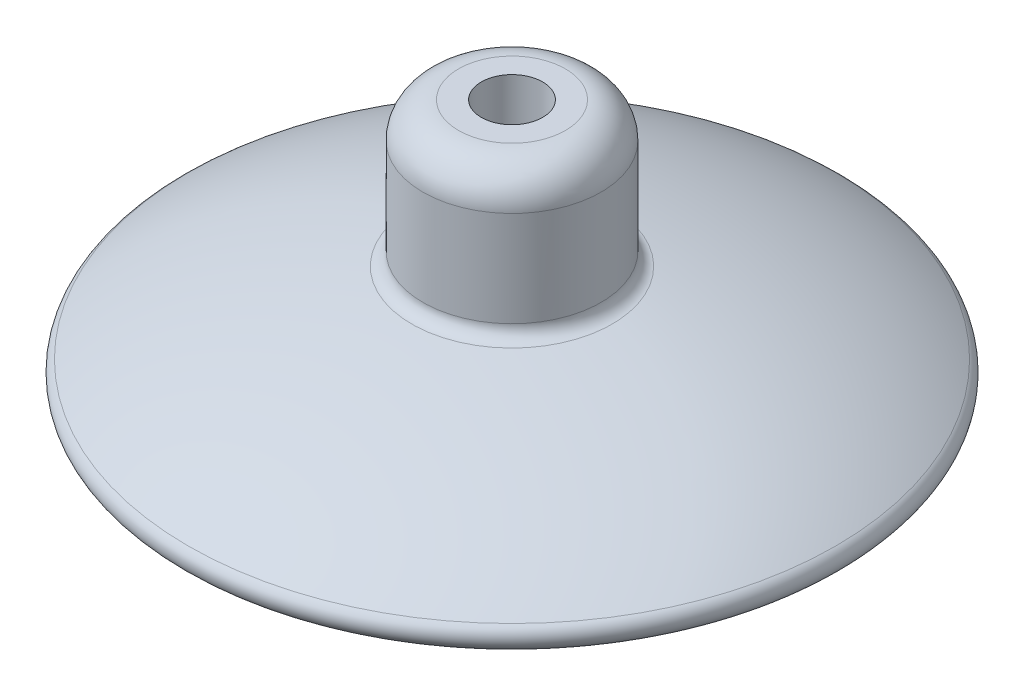
SolidWorks part; units mm, degrees
ref_plane "Front Plane" through (0, 0, 0) normal (0, 0, 1) x (1, 0, 0)
ref_plane "Top Plane" through (0, 0, 0) normal (0, 1, 0) x (1, 0, 0)
ref_plane "Right Plane" through (0, 0, 0) normal (1, 0, 0) x (0, 0, -1)
sketch "Sketch1" plane through (0, 0, 0) normal (0, 1, 0) x (1, 0, 0)
  circle A0 centre (0, 0) radius 5
  dimension "D1" = 10
extrude "Boss-Extrude1" add sketch "Sketch1" along normal blind 8
sketch "Sketch2" plane through (0, 0, 0) normal (0, 0, 1) x (1, 0, 0)
  line L0 (0, 0) -> (-5, 0)
  line L1 (-5, 0) -> (5, 0) construction
  line L2 (0, 0) -> (0, -6)
  line L3 (0, -6) -> (-20, -6)
  spline S0 degree 2 poles (-20, -6) (-14.6563, -1.492) (-5, 0) knots 0 0 0 1 1 1
  dimension "D1" = 20
  dimension "D2" = 6
revolve "Revolve1" add sketch "Sketch2" angle 360 about L2
sketch "Sketch3" plane through (0, -6, 0) normal (0, -1, 0) x (1, 0, 0)
  circle A0 centre (0, 0) radius 3.45
  dimension "D1" = 6.9
extrude "Cut-Extrude1" cut sketch "Sketch3" against normal blind 4.19
sketch "Sketch4" plane through (0, -1.81, 0) normal (0, -1, 0) x (1, 0, 0)
  circle A0 centre (0, 0) radius 1.725
  dimension "D1" = 3.45
extrude "Cut-Extrude2" cut sketch "Sketch4" against normal through all
fillet "Fillet1" radius 0.75 2 edges at (-5, 0, 0) (-20, -6, 0)
fillet "Fillet2" radius 2 1 edges at (0, 8, 5)
